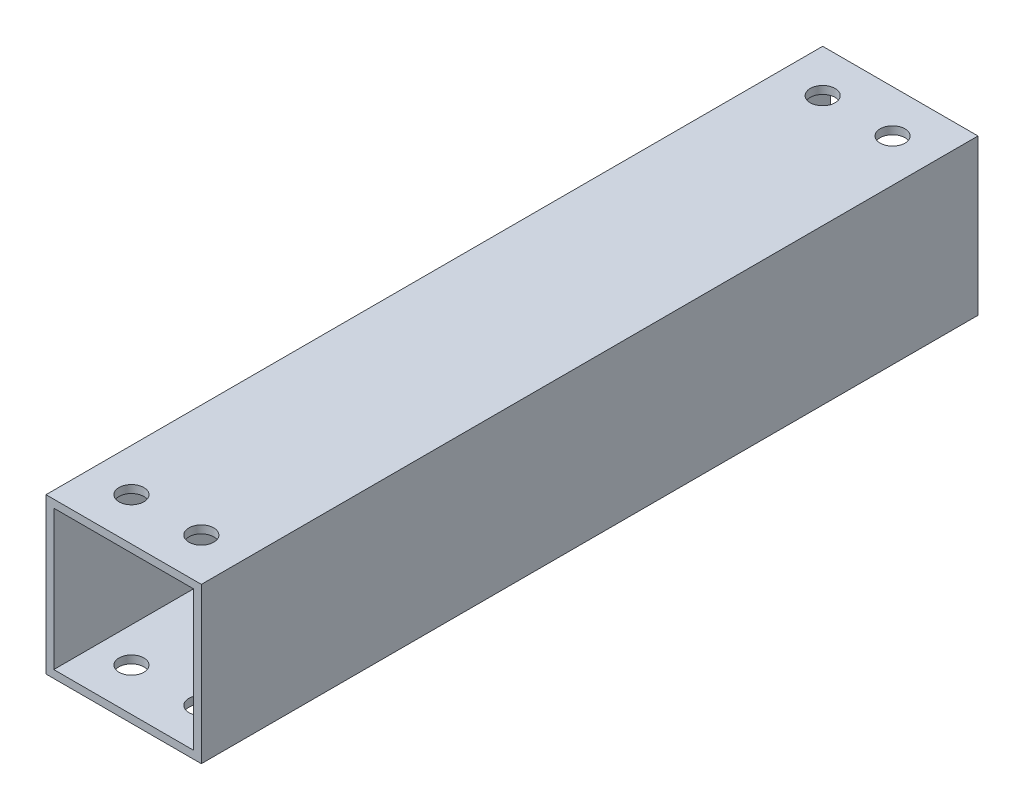
SolidWorks part; units mm, degrees
material "6061-T6 (SS)"
ref_plane "前视基准面" through (0, 0, 0) normal (0, 0, 1) x (1, 0, 0)
ref_plane "上视基准面" through (0, 0, 0) normal (0, 1, 0) x (1, 0, 0)
ref_plane "右视基准面" through (0, 0, 0) normal (1, 0, 0) x (0, 0, -1)
sketch "草图1" plane through (0, 0, 0) normal (0, 0, 1) x (1, 0, 0)
  line L1 (-10, 10) -> (10, 10)
  line L2 (-10, 10) -> (-10, -10)
  line L3 (-10, -10) -> (10, -10)
  line L4 (10, 10) -> (10, -10)
  line L5 (0, -10) -> (0, 10) construction
  line L6 (-10, 0) -> (10, 0) construction
  line L7 (-9, 9) -> (9, 9)
  line L8 (-9, 9) -> (-9, -9)
  line L9 (-9, -9) -> (9, -9)
  line L10 (9, 9) -> (9, -9)
  line L11 (0, -9) -> (0, 9) construction
  line L12 (-9, 0) -> (9, 0) construction
  point P0 (0, 0)
  point P4 (0, 0)
  dimension "D1" = 20
  dimension "D2" = 20
  dimension "D3" = 18
  dimension "D4" = 18
extrude "凸台-拉伸1" add sketch "草图1" along normal blind 100
sketch "草图2" plane through (0, 10, 0) normal (0, 1, 0) x (1, 0, 0)
  line L0 (10, -100) -> (10, 0) construction
  line L1 (-10, -100) -> (10, -100) construction
  line L2 (-10, -100) -> (-10, -80) construction
  line L3 (-10, -80) -> (10, -80) construction
  line L4 (10, -100) -> (10, -80) construction
  line L5 (-10, -100) -> (10, -80) construction
  line L6 (-10, -80) -> (10, -100) construction
  line L8 (-4.5, -85.5) -> (4.5, -85.5) construction
  line L9 (-4.5, -85.5) -> (-4.5, -94.5) construction
  line L10 (-4.5, -94.5) -> (4.5, -94.5) construction
  line L11 (4.5, -85.5) -> (4.5, -94.5) construction
  line L12 (0, -94.5) -> (0, -85.5) construction
  line L13 (-4.5, -90) -> (4.5, -90) construction
  line L14 (-10, 0) -> (10, 0) construction
  line L15 (-10, 0) -> (-10, -100) construction
  line L16 (-10, -100) -> (10, -100) construction
  line L17 (10, 0) -> (10, -100) construction
  line L18 (0, -100) -> (0, 0) construction
  line L19 (-10, -50) -> (10, -50) construction
  circle A2 centre (4.5, -94.5) radius 1.6
  circle A3 centre (-4.5, -94.5) radius 1.6
  circle A4 centre (-4.5, -5.5) radius 1.6
  circle A5 centre (4.5, -5.5) radius 1.6
  point P4 (0, -90)
  point P8 (0, -90)
  point P164 (0, -50)
  dimension "D1" = 20
  dimension "D2" = 9
  dimension "D3" = 9
extrude "切除-拉伸1" cut sketch "草图2" against normal through all
